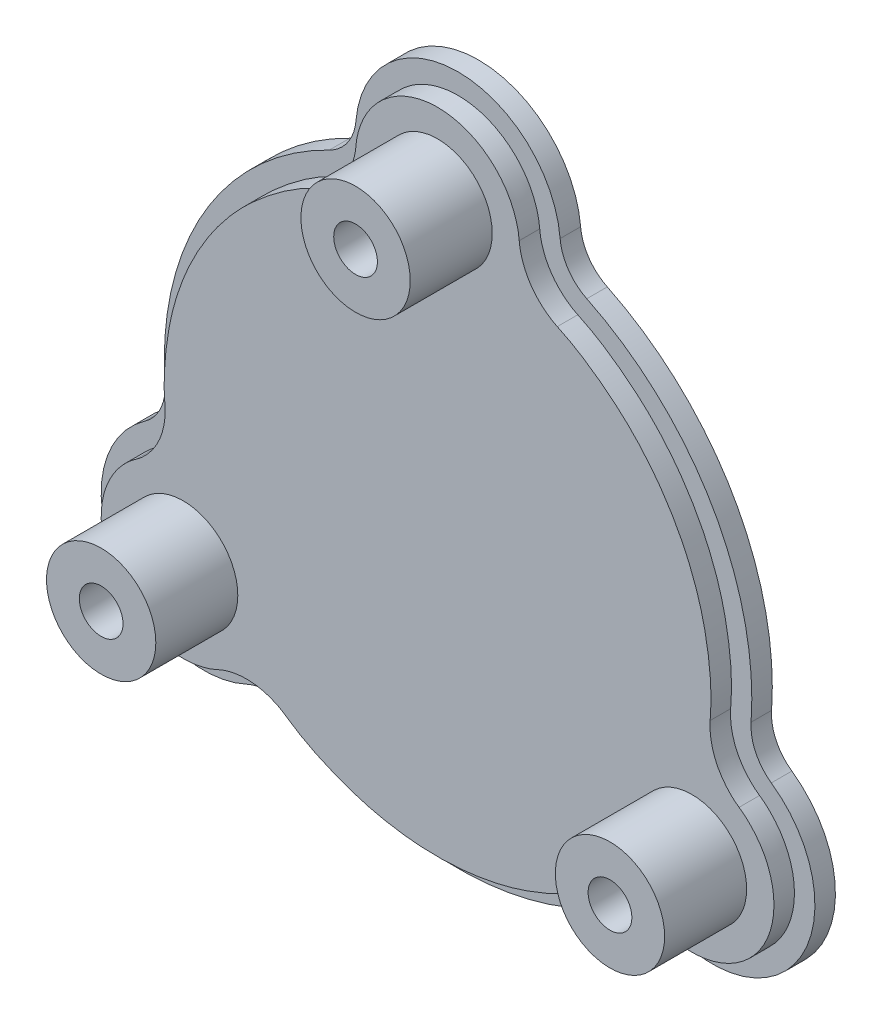
SolidWorks part; units mm, degrees
material "PBT General Purpose"
ref_plane "Front Plane" through (0, 0, 0) normal (0, 0, 1) x (1, 0, 0)
ref_plane "Top Plane" through (0, 0, 0) normal (0, 1, 0) x (1, 0, 0)
ref_plane "Right Plane" through (0, 0, 0) normal (1, 0, 0) x (0, 0, -1)
sketch "Sketch1" plane through (0, 0, 0) normal (0, 0, 1) x (1, 0, 0)
  line L0 (0, 43) -> (0, 82.2622) construction
  line L3 (-37.2391, -21.5) -> (-76.1188, -43.9472) construction
  line L5 (37.2391, -21.5) -> (85.3817, -49.2952) construction
  arc A0 (42.895, -3.0038) -> (18.8462, 38.65) centre (0, 0) ccw
  arc A1 (14.9415, 44.324) -> (-14.9415, 44.324) centre (0, 43) ccw
  arc A2 (-45.8564, -9.2223) -> (-30.915, -35.1017) centre (-37.2391, -21.5) ccw
  arc A3 (30.915, -35.1017) -> (45.8564, -9.2223) centre (37.2391, -21.5) ccw
  arc A4 (-24.0488, -35.6462) -> (24.0488, -35.6462) centre (0, 0) ccw
  arc A5 (-18.8462, 38.65) -> (-42.895, -3.0038) centre (0, 0) ccw
  arc A6 (-14.9415, 44.324) -> (-18.8462, 38.65) centre (-21.9141, 44.9419) cw
  arc A7 (14.9415, 44.324) -> (18.8462, 38.65) centre (21.9141, 44.9419) ccw
  arc A8 (-45.8564, -9.2223) -> (-42.895, -3.0038) centre (-49.8779, -3.4927) ccw
  arc A9 (-30.915, -35.1017) -> (-24.0488, -35.6462) centre (-27.9637, -41.4491) cw
  arc A10 (30.915, -35.1017) -> (24.0488, -35.6462) centre (27.9637, -41.4491) ccw
  arc A11 (45.8564, -9.2223) -> (42.895, -3.0038) centre (49.8779, -3.4927) cw
  dimension "D3" = 86
  dimension "D4" = 15
  dimension "D5" = 7
  dimension "D6" = 7
  dimension "D7" = 7
  dimension "D8" = 7
  dimension "D9" = 7
  dimension "D10" = 7
  dimension "D11" = 43
  dimension "D1" = 120
  dimension "D2" = 120
  dimension "D12" = 43
  dimension "D13" = 43
extrude "Boss-Extrude1" add sketch "Sketch1" along normal blind 3
sketch3d "3DSketch1"
  spline S0 degree 5 poles (-860.3137, -1760.9374, 3) (-312.0144, -671.2908, 3) (-45.6684, -133.8647, 3) (34.2606, 38.4536, 3) (22.9528, 32.5921, 3) (16.6076, 36.45, 3) (16.4124, 36.5792, 3) (15.9342, 36.9172, 3) (15.4777, 37.2817, 3) (15.2128, 37.5106, 3) (14.7035, 37.9899, 3) (14.2399, 38.5149, 3) (14.0199, 38.7878, 3) (13.6041, 39.3524, 3) (13.2379, 39.9504, 3) (13.068, 40.257, 3) (12.7629, 40.8717, 3) (12.515, 41.5106, 3) (12.4065, 41.8284, 3) (12.2465, 42.3606, 3) (12.1161, 42.9018, 3) (12.0708, 43.1168, 3) (12.0158, 43.434, 3) (11.9653, 43.8969, 3) (11.9465, 44.1432, 3) (11.9261, 44.3892, 3) (11.8945, 44.6341, 3) (1998.7254, 253.2621, 2.9942) knots -3.436068 -3.436068 -3.436068 -3.436068 -3.436068 -3.436068 0.056255 0.056255 0.056255 0.1697 0.1697 0.1697 0.339869 0.339869 0.339869 0.510038 0.510038 0.510038 0.680206 0.680206 0.680206 0.843495 0.843495 0.843495 0.95006 0.95006 0.95006 0.999902 1.070242 1.070242 1.070242 1.070242 1.070242 1.070242 only from (17.527, 35.9556, 3) to (11.9531, 44.0602, 3)
  spline S1 degree 5 poles (2004.2193, 217.1358, 3) (789.3192, 95.3125, 3) (192.1624, 39.5792, 3) (3.2218, 27.5195, 3) (13.3064, 37.0339, 3) (11.7927, 45.3074, 3) (11.7316, 45.5816, 3) (11.5576, 46.2624, 3) (11.3448, 46.9302, 3) (11.2018, 47.3252, 3) (10.883, 48.1015, 3) (10.4934, 48.8465, 3) (10.2818, 49.2102, 3) (9.8273, 49.9182, 3) (9.3135, 50.5839, 3) (9.0424, 50.9053, 3) (8.473, 51.5236, 3) (7.8513, 52.0897, 3) (7.5283, 52.359, 3) (6.8595, 52.8686, 3) (6.1487, 53.3178, 3) (5.7837, 53.5267, 3) (5.0365, 53.9122, 3) (4.2584, 54.2308, 3) (3.8626, 54.373, 3) (3.0597, 54.6224, 3) (2.238, 54.8006, 3) (1.8235, 54.8718, 3) (0.9894, 54.9776, 3) (0.1492, 55.0101, 3) (-0.2713, 55.0079, 3) (-1.1111, 54.9669, 3) (-1.9441, 54.8526, 3) (-2.3579, 54.7773, 3) (-3.1777, 54.5907, 3) (-3.9781, 54.3331, 3) (-4.3724, 54.1869, 3) (-5.1472, 53.8604, 3) (-5.8905, 53.4674, 3) (-6.2533, 53.2547, 3) (-6.9595, 52.7984, 3) (-7.623, 52.2819, 3) (-7.9433, 52.0094, 3) (-8.5592, 51.437, 3) (-9.1224, 50.8129, 3) (-9.3902, 50.4888, 3) (-9.8971, 49.8179, 3) (-10.3445, 49.1053, 3) (-10.5523, 48.7395, 3) (-10.9306, 47.9979, 3) (-11.2391, 47.226, 3) (-11.376, 46.8375, 3) (-11.5787, 46.1836, 3) (-11.7442, 45.5178, 3) (-11.802, 45.2514, 3) (-13.2505, 37.1334, 3) (-3.5916, 27.8328, 3) (-192.9693, 39.9975, 3) (-790.1686, 95.5846, 3) (-2004.2932, 216.8589, 3) knots -1.121492 -1.121492 -1.121492 -1.121492 -1.121492 -1.121492 0.019647 0.019647 0.019647 0.058998 0.058998 0.058998 0.118025 0.118025 0.118025 0.177051 0.177051 0.177051 0.236078 0.236078 0.236078 0.295104 0.295104 0.295104 0.354131 0.354131 0.354131 0.413157 0.413157 0.413157 0.472184 0.472184 0.472184 0.53121 0.53121 0.53121 0.590237 0.590237 0.590237 0.649263 0.649263 0.649263 0.70829 0.70829 0.70829 0.767316 0.767316 0.767316 0.826343 0.826343 0.826343 0.885369 0.885369 0.885369 0.943255 0.943255 0.943255 0.981465 0.981465 0.981465 2.100941 2.100941 2.100941 2.100941 2.100941 2.100941 only from (11.9531, 44.0602, 3) to (-11.9532, 44.0592, 3)
  spline S2 degree 5 poles (1979.9765, -133.949, 3) (766.3526, -11.0894, 3) (169.2376, 45.6947, 3) (-20.2646, 58.7915, 3) (-10.7503, 50.3238, 3) (-12.0869, 43.019, 3) (-12.1378, 42.7906, 3) (-12.2828, 42.2232, 3) (-12.4601, 41.6666, 3) (-12.5793, 41.3374, 3) (-12.845, 40.6905, 3) (-13.1697, 40.07, 3) (-13.3461, 39.767, 3) (-13.7248, 39.1769, 3) (-14.1525, 38.6212, 3) (-14.3783, 38.3531, 3) (-14.8433, 37.8484, 3) (-15.3516, 37.3887, 3) (-15.6097, 37.1738, 3) (-16.0496, 36.8343, 3) (-16.5085, 36.5191, 3) (-16.6931, 36.4, 3) (-22.807, 32.7591, 3) (-33.431, 37.9761, 3) (46.96, -135.0822, 3) (312.9624, -672.6898, 3) (859.5004, -1761.281, 3) knots -3.434333 -3.434333 -3.434333 -3.434333 -3.434333 -3.434333 0.056702 0.056702 0.056702 0.170106 0.170106 0.170106 0.340211 0.340211 0.340211 0.510317 0.510317 0.510317 0.680422 0.680422 0.680422 0.84365 0.84365 0.84365 0.950176 0.950176 0.950176 4.299461 4.299461 4.299461 4.299461 4.299461 4.299461 only from (-11.9532, 44.0592, 3) to (-17.5313, 35.9535, 3)
  spline S3 degree 5 poles (-846.1484, 1855.3944, 3) (-303.1451, 751.1079, 3) (-47.1755, 209.3347, 3) (19.9464, 37.6554, 3) (-4.7962, 43.9566, 3) (-21.2263, 33.9675, 3) (-22.0072, 33.4507, 3) (-23.9198, 32.0985, 3) (-25.7454, 30.6405, 3) (-26.8049, 29.7251, 3) (-28.8422, 27.808, 3) (-30.6979, 25.7079, 3) (-31.5785, 24.6163, 3) (-33.2415, 22.3579, 3) (-34.701, 19.9659, 3) (-35.3785, 18.7392, 3) (-36.6258, 16.23, 3) (-37.6521, 13.62, 3) (-38.1073, 12.2934, 3) (-38.8681, 9.7015, 3) (-39.3939, 7.0562, 3) (-39.5966, 5.7731, 3) (-39.8536, 3.6557, 3) (-39.9977, 1.5244, 3) (-40.0312, 0.6913, 3) (-40.144, -17.0171, 3) (-24.9969, -33.9024, 3) (-209.8744, -60.7448, 3) (-807.2354, -109.8368, 3) (-2030.2513, -192.6769, 3) knots -1.874629 -1.874629 -1.874629 -1.874629 -1.874629 -1.874629 0.04914 0.04914 0.04914 0.14742 0.14742 0.14742 0.294839 0.294839 0.294839 0.442259 0.442259 0.442259 0.589678 0.589678 0.589678 0.737098 0.737098 0.737098 0.873872 0.873872 0.873872 0.961506 0.961506 0.961506 2.737832 2.737832 2.737832 2.737832 2.737832 2.737832 only from (-17.5313, 35.9535, 3) to (-39.9023, -2.7942, 3)
  spline S4 degree 5 poles (1955.1838, 135.4163, 3) (737.3662, 65.4332, 3) (138.7654, 27.3824, 3) (-50.4321, 10.4438, 3) (-39.702, 3.5817, 3) (-39.8704, -3.8424, 3) (-39.8847, -4.0761, 3) (-39.9384, -4.6592, 3) (-40.0258, -5.2368, 3) (-40.0915, -5.5806, 3) (-40.2519, -6.2613, 3) (-40.4748, -6.9253, 3) (-40.6012, -7.2523, 3) (-40.8822, -7.8947, 3) (-41.217, -8.5108, 3) (-41.3976, -8.8113, 3) (-41.7773, -9.3829, 3) (-42.2067, -9.917, 3) (-42.4277, -10.1699, 3) (-42.8086, -10.5745, 3) (-43.2121, -10.958, 3) (-43.3756, -11.1048, 3) (-48.8392, -15.6639, 3) (-60.1527, -12.1868, 3) (46.5129, -170.4093, 3) (393.9342, -659.3649, 3) (1105.2373, -1648.1936, 3) knots -3.434333 -3.434333 -3.434333 -3.434333 -3.434333 -3.434333 0.056702 0.056702 0.056702 0.170106 0.170106 0.170106 0.340211 0.340211 0.340211 0.510317 0.510317 0.510317 0.680422 0.680422 0.680422 0.84365 0.84365 0.84365 0.950176 0.950176 0.950176 4.299461 4.299461 4.299461 4.299461 4.299461 4.299461 only from (-39.9023, -2.7942, 3) to (-44.133, -11.6779, 3)
  spline S5 degree 5 poles (-1190.1487, 1627.1296, 3) (-477.2005, 635.9112, 3) (-130.3573, 146.6272, 3) (-25.4435, -10.9696, 3) (-38.7255, -6.9933, 3) (-45.1337, -12.4409, 3) (-45.3406, -12.631, 3) (-45.8432, -13.122, 3) (-46.3152, -13.6403, 3) (-46.5857, -13.9616, 3) (-47.0986, -14.6258, 3) (-47.549, -15.3357, 3) (-47.7582, -15.7008, 3) (-48.1441, -16.4484, 3) (-48.4637, -17.2262, 3) (-48.6065, -17.6217, 3) (-48.8573, -18.424, 3) (-49.0366, -19.2454, 3) (-49.1083, -19.6598, 3) (-49.2153, -20.4939, 3) (-49.2489, -21.334, 3) (-49.2474, -21.7545, 3) (-49.2076, -22.5944, 3) (-49.0944, -23.4275, 3) (-49.0197, -23.8414, 3) (-48.8342, -24.6615, 3) (-48.5777, -25.4622, 3) (-48.4321, -25.8567, 3) (-48.1067, -26.632, 3) (-47.7147, -27.3758, 3) (-47.5026, -27.7389, 3) (-47.0472, -28.4457, 3) (-46.5317, -29.11, 3) (-46.2596, -29.4306, 3) (-45.6881, -30.0473, 3) (-45.0648, -30.6117, 3) (-44.741, -30.88, 3) (-44.0709, -31.3878, 3) (-43.3589, -31.835, 3) (-42.9933, -32.0429, 3) (-42.245, -32.4263, 3) (-41.4659, -32.7427, 3) (-41.0698, -32.8838, 3) (-40.2661, -33.131, 3) (-39.4441, -33.3067, 3) (-39.0295, -33.3765, 3) (-38.195, -33.4801, 3) (-37.3542, -33.5112, 3) (-36.9335, -33.5083, 3) (-36.1021, -33.4651, 3) (-35.2794, -33.3464, 3) (-34.8745, -33.2707, 3) (-34.2069, -33.1193, 3) (-33.5475, -32.9297, 3) (-33.2878, -32.8465, 3) (-25.5333, -30.0419, 3) (-22.3081, -17.0269, 3) (61.8456, -187.1147, 3) (312.3048, -732.0966, 3) (814.3392, -1844.1937, 3) knots -1.12143 -1.12143 -1.12143 -1.12143 -1.12143 -1.12143 0.019675 0.019675 0.019675 0.059025 0.059025 0.059025 0.11805 0.11805 0.11805 0.177075 0.177075 0.177075 0.236099 0.236099 0.236099 0.295124 0.295124 0.295124 0.354149 0.354149 0.354149 0.413174 0.413174 0.413174 0.472199 0.472199 0.472199 0.531224 0.531224 0.531224 0.590248 0.590248 0.590248 0.649273 0.649273 0.649273 0.708298 0.708298 0.708298 0.767323 0.767323 0.767323 0.826348 0.826348 0.826348 0.885373 0.885373 0.885373 0.943257 0.943257 0.943257 0.981466 0.981466 0.981466 2.100909 2.100909 2.100909 2.100909 2.100909 2.100909 only from (-44.133, -11.6779, 3) to (-32.1798, -32.3813, 3)
  spline S6 degree 5 poles (-873.9817, 1781.6769, 3) (-373.5713, 669.2226, 3) (-124.1912, 123.716, 3) (-40.7826, -46.9454, 3) (-38.2065, -34.472, 3) (-31.2121, -31.9771, 3) (-30.9888, -31.907, 3) (-30.425, -31.7488, 3) (-29.8543, -31.6241, 3) (-29.5097, -31.5627, 3) (-28.8165, -31.4693, 3) (-28.1168, -31.4403, 3) (-27.7662, -31.4415, 3) (-27.0658, -31.4745, 3) (-26.3707, -31.5671, 3) (-26.0256, -31.6285, 3) (-25.356, -31.7789, 3) (-24.7038, -31.9892, 3) (-24.3886, -32.1053, 3) (-23.8746, -32.3165, 3) (-23.3723, -32.5563, 3) (-23.1768, -32.6567, 3) (-22.8959, -32.8138, 3) (-22.626, -32.9881, 3) (-22.348, -33.173, 3) (-22.0739, -33.364, 3) (-21.7909, -33.5411, 3) (-24.1044, -37.5263, 3) (1068.169, 1643.053, 2.9998) knots -3.433006 -3.433006 -3.433006 -3.433006 -3.433006 -3.433006 0.05668 0.05668 0.05668 0.17004 0.17004 0.17004 0.34008 0.34008 0.34008 0.51012 0.51012 0.51012 0.68016 0.68016 0.68016 0.843325 0.843325 0.843325 0.94981 0.94981 0.94981 0.999615 0.999615 1.112235 1.112235 1.112235 1.112235 1.112235 1.112235 only from (-32.1798, -32.3813, 3) to (-22.3677, -33.1615, 3)
  spline S7 degree 5 poles (-1183.7516, -1660.4941, 3) (-498.9088, -638.0895, 3) (-157.7022, -145.5234, 3) (-42.5837, -1.5535, 3) (-35.6695, -26.1319, 3) (-18.8036, -35.3663, 3) (-17.9656, -35.7841, 3) (-15.8382, -36.7644, 3) (-13.6627, -37.6165, 3) (-12.3403, -38.0763, 3) (-9.6613, -38.8821, 3) (-6.9148, -39.4391, 3) (-5.5291, -39.6559, 3) (-2.7418, -39.9669, 3) (0.0596, -40.0349, 3) (1.4606, -40.0083, 3) (4.2574, -39.8339, 3) (7.0308, -39.4177, 3) (8.4072, -39.1486, 3) (11.0323, -38.5115, 3) (13.5861, -37.6442, 3) (14.7986, -37.1783, 3) (16.7609, -36.3421, 3) (18.6787, -35.4012, 3) (19.4169, -35.0137, 3) (34.8093, -26.2572, 3) (41.8588, -4.6967, 3) (157.5442, -151.3847, 3) (498.7411, -644.1707, 3) (1181.9934, -1661.9178, 3) knots -1.874873 -1.874873 -1.874873 -1.874873 -1.874873 -1.874873 0.04906 0.04906 0.04906 0.147348 0.147348 0.147348 0.29478 0.29478 0.29478 0.442212 0.442212 0.442212 0.589644 0.589644 0.589644 0.737076 0.737076 0.737076 0.873861 0.873861 0.873861 0.961502 0.961502 0.961502 2.73798 2.73798 2.73798 2.73798 2.73798 2.73798 only from (-22.3677, -33.1615, 3) to (22.371, -33.1593, 3)
  spline S8 degree 5 poles (-1094.8644, 1625.5285, 3) (-425.3493, 605.8603, 3) (-93.0964, 106.4829, 3) (16.1715, -48.8973, 3) (16.7492, -36.1738, 3) (23.2628, -32.6076, 3) (23.4723, -32.5031, 3) (24.0042, -32.258, 3) (24.5481, -32.045, 3) (24.8787, -31.93, 3) (25.5484, -31.7285, 3) (26.2349, -31.5896, 3) (26.5813, -31.5355, 3) (27.2781, -31.4577, 3) (27.9791, -31.4395, 3) (28.3296, -31.4458, 3) (29.0145, -31.4888, 3) (29.6917, -31.5936, 3) (30.0213, -31.6585, 3) (30.5621, -31.7861, 3) (31.096, -31.9437, 3) (31.3048, -32.012, 3) (31.607, -32.1229, 3) (32.0421, -32.3146, 3) (32.2733, -32.426, 3) (32.5055, -32.5353, 3) (32.7428, -32.6329, 3) (-779.0835, -1858.7335, 2.9474) knots -3.433937 -3.433937 -3.433937 -3.433937 -3.433937 -3.433937 0.056695 0.056695 0.056695 0.170086 0.170086 0.170086 0.340172 0.340172 0.340172 0.510258 0.510258 0.510258 0.680344 0.680344 0.680344 0.843553 0.843553 0.843553 0.950067 0.950067 0.950067 0.999885 1.074913 1.074913 1.074913 1.074913 1.074913 1.074913 only from (22.371, -33.1593, 3) to (32.1809, -32.3818, 3)
  spline S9 degree 5 poles (-814.0955, -1844.3412, 3) (-312.1289, -731.2536, 3) (-61.8077, -186.2134, 3) (22.2216, -16.5495, 3) (25.419, -30.0406, 3) (33.341, -32.8665, 3) (33.609, -32.9506, 3) (34.2856, -33.1404, 3) (34.9704, -33.29, 3) (35.3839, -33.3637, 3) (36.2157, -33.4757, 3) (37.0556, -33.5108, 3) (37.4763, -33.5094, 3) (38.3168, -33.4698, 3) (39.1502, -33.3577, 3) (39.5641, -33.2836, 3) (40.3843, -33.0996, 3) (41.1853, -32.8443, 3) (41.5801, -32.6991, 3) (42.3559, -32.3748, 3) (43.1002, -31.9838, 3) (43.4637, -31.7722, 3) (44.1711, -31.3178, 3) (44.836, -30.8032, 3) (45.1571, -30.5316, 3) (45.7746, -29.961, 3) (46.3398, -29.3385, 3) (46.6086, -29.0151, 3) (47.1173, -28.3456, 3) (47.5655, -27.6342, 3) (47.7739, -27.269, 3) (48.1583, -26.5212, 3) (48.4758, -25.7426, 3) (48.6174, -25.3467, 3) (48.8658, -24.5434, 3) (49.0429, -23.7214, 3) (49.1134, -23.3068, 3) (49.2181, -22.4726, 3) (49.2493, -21.6324, 3) (49.2466, -21.2119, 3) (49.2045, -20.3721, 3) (49.089, -19.5392, 3) (49.0131, -19.1256, 3) (48.8254, -18.306, 3) (48.5665, -17.5063, 3) (48.4196, -17.1123, 3) (48.0921, -16.3378, 3) (47.6987, -15.5941, 3) (47.4858, -15.2312, 3) (47.0327, -14.5327, 3) (46.5185, -13.8796, 3) (46.2505, -13.5669, 3) (45.7856, -13.0644, 3) (45.2917, -12.5881, 3) (45.0898, -12.4048, 3) (38.7837, -7.0915, 3) (25.8998, -10.806, 3) (131.1235, 147.1175, 3) (477.8628, 636.5135, 3) (1189.9515, 1627.3385, 3) knots -1.121517 -1.121517 -1.121517 -1.121517 -1.121517 -1.121517 0.019642 0.019642 0.019642 0.058994 0.058994 0.058994 0.11802 0.11802 0.11802 0.177047 0.177047 0.177047 0.236074 0.236074 0.236074 0.295101 0.295101 0.295101 0.354128 0.354128 0.354128 0.413154 0.413154 0.413154 0.472181 0.472181 0.472181 0.531208 0.531208 0.531208 0.590235 0.590235 0.590235 0.649262 0.649262 0.649262 0.708288 0.708288 0.708288 0.767315 0.767315 0.767315 0.826342 0.826342 0.826342 0.885369 0.885369 0.885369 0.943255 0.943255 0.943255 0.981465 0.981465 0.981465 2.100947 2.100947 2.100947 2.100947 2.100947 2.100947 only from (32.1809, -32.3818, 3) to (44.133, -11.6779, 3)
  spline S10 degree 5 poles (-1105.9949, -1647.7403, 3) (-392.7814, -658.1381, 3) (-45.0464, -169.4119, 3) (61.0472, -11.8461, 3) (48.9569, -15.8518, 3) (43.299, -11.042, 3) (43.1266, -10.8836, 3) (42.7077, -10.4744, 3) (42.3144, -10.0425, 3) (42.0889, -9.7748, 3) (41.6615, -9.2212, 3) (41.2865, -8.6297, 3) (41.1123, -8.3255, 3) (40.7906, -7.7024, 3) (40.5232, -7.0542, 3) (40.4039, -6.7246, 3) (40.1994, -6.0695, 3) (40.0554, -5.3995, 3) (39.9983, -5.0685, 3) (39.9242, -4.5178, 3) (39.8807, -3.9628, 3) (39.8699, -3.7434, 3) (39.8656, -3.4215, 3) (39.8815, -3.1006, 3) (39.9028, -2.7638, 3) (39.9316, -2.4274, 3) (39.9432, -2.09, 3) (44.6594, -2.1031, 3) (-1956.8344, 103.5873, 2.9998) knots -3.432962 -3.432962 -3.432962 -3.432962 -3.432962 -3.432962 0.056679 0.056679 0.056679 0.170038 0.170038 0.170038 0.340075 0.340075 0.340075 0.510113 0.510113 0.510113 0.68015 0.68015 0.68015 0.843313 0.843313 0.843313 0.949796 0.949796 0.949796 0.9996 0.9996 1.113983 1.113983 1.113983 1.113983 1.113983 1.113983 only from (44.133, -11.6779, 3) to (39.9026, -2.7901, 3)
  spline S11 degree 5 poles (2029.9204, -194.9129, 3) (802.0618, -113.0234, 3) (204.8794, -63.8126, 3) (22.6372, -36.1019, 3) (40.4656, -17.8248, 3) (40.0299, 1.3988, 3) (39.9728, 2.3334, 3) (39.758, 4.6659, 3) (39.4082, 6.9759, 3) (39.1451, 8.3511, 3) (38.5036, 11.0741, 3) (37.6127, 13.7312, 3) (37.1076, 15.0396, 3) (35.9833, 17.609, 3) (34.6415, 20.069, 3) (33.9179, 21.2691, 3) (32.3685, 23.6039, 3) (30.6213, 25.7977, 3) (29.7001, 26.8552, 3) (27.8358, 28.81, 3) (25.8078, 30.588, 3) (24.798, 31.4051, 3) (23.0927, 32.6864, 3) (21.319, 33.8768, 3) (20.6143, 34.3224, 3) (19.5804, 34.9281, 3) (18.5148, 35.4715, 3) (17.8064, 35.8222, 3) (17.0933, 36.1638, 3) (16.3856, 36.516, 3) (14.6341, 34.006, 3) (919.7812, 1817.2964, 2.9992) knots -1.874697 -1.874697 -1.874697 -1.874697 -1.874697 -1.874697 0.049052 0.049052 0.049052 0.147331 0.147331 0.147331 0.294748 0.294748 0.294748 0.442165 0.442165 0.442165 0.589583 0.589583 0.589583 0.737 0.737 0.737 0.873772 0.873772 0.873772 0.961405 0.961405 0.961405 0.999899 0.999899 1.044758 1.044758 1.044758 1.044758 1.044758 1.044758 only from (39.9026, -2.7901, 3) to (17.527, 35.9556, 3)
  spline S12 degree 5 poles (17.527, 35.9556, 3) (17.4231, 36.0062, 3) (17.3193, 36.0569, 3) (17.2158, 36.1084, 3) (16.9062, 36.2684, 3) (16.6076, 36.45, 3) (16.4124, 36.5792, 3) (15.9342, 36.9172, 3) (15.4777, 37.2817, 3) (15.2128, 37.5106, 3) (14.7035, 37.9899, 3) (14.2399, 38.5149, 3) (14.0199, 38.7878, 3) (13.6041, 39.3524, 3) (13.2379, 39.9504, 3) (13.068, 40.257, 3) (12.7629, 40.8717, 3) (12.515, 41.5106, 3) (12.4065, 41.8284, 3) (12.2465, 42.3606, 3) (12.1161, 42.9018, 3) (12.0708, 43.1168, 3) (12.0158, 43.434, 3) (11.9809, 43.7535, 3) (11.9712, 43.8556, 3) (11.9621, 43.9578, 3) (11.9531, 44.06, 3) (11.9531, 44.0602, 3) knots 0 0 0 0 0 0 0.056255 0.056255 0.056255 0.1697 0.1697 0.1697 0.339869 0.339869 0.339869 0.510038 0.510038 0.510038 0.680206 0.680206 0.680206 0.843495 0.843495 0.843495 0.95006 0.95006 0.95006 0.999902 1 1 1 1 1 1
  spline S13 degree 5 poles (11.9531, 44.0602, 3) (11.9408, 44.1993, 3) (11.9284, 44.3383, 3) (11.915, 44.4773, 3) (11.8683, 44.8939, 3) (11.7927, 45.3074, 3) (11.7316, 45.5816, 3) (11.5576, 46.2624, 3) (11.3448, 46.9302, 3) (11.2018, 47.3252, 3) (10.883, 48.1015, 3) (10.4934, 48.8465, 3) (10.2818, 49.2102, 3) (9.8273, 49.9182, 3) (9.3135, 50.5839, 3) (9.0424, 50.9053, 3) (8.473, 51.5236, 3) (7.8513, 52.0897, 3) (7.5283, 52.359, 3) (6.8595, 52.8686, 3) (6.1487, 53.3178, 3) (5.7837, 53.5267, 3) (5.0365, 53.9122, 3) (4.2584, 54.2308, 3) (3.8626, 54.373, 3) (3.0597, 54.6224, 3) (2.238, 54.8006, 3) (1.8235, 54.8718, 3) (0.9894, 54.9776, 3) (0.1492, 55.0101, 3) (-0.2713, 55.0079, 3) (-1.1111, 54.9669, 3) (-1.9441, 54.8526, 3) (-2.3579, 54.7773, 3) (-3.1777, 54.5907, 3) (-3.9781, 54.3331, 3) (-4.3724, 54.1869, 3) (-5.1472, 53.8604, 3) (-5.8905, 53.4674, 3) (-6.2533, 53.2547, 3) (-6.9595, 52.7984, 3) (-7.623, 52.2819, 3) (-7.9433, 52.0094, 3) (-8.5592, 51.437, 3) (-9.1224, 50.8129, 3) (-9.3902, 50.4888, 3) (-9.8971, 49.8179, 3) (-10.3445, 49.1053, 3) (-10.5523, 48.7395, 3) (-10.9306, 47.9979, 3) (-11.2391, 47.226, 3) (-11.376, 46.8375, 3) (-11.5787, 46.1836, 3) (-11.7442, 45.5178, 3) (-11.802, 45.2514, 3) (-11.873, 44.8534, 3) (-11.9173, 44.4527, 3) (-11.9299, 44.3216, 3) (-11.9415, 44.1904, 3) (-11.9532, 44.0592, 3) knots 0 0 0 0 0 0 0.019647 0.019647 0.019647 0.058998 0.058998 0.058998 0.118025 0.118025 0.118025 0.177051 0.177051 0.177051 0.236078 0.236078 0.236078 0.295104 0.295104 0.295104 0.354131 0.354131 0.354131 0.413157 0.413157 0.413157 0.472184 0.472184 0.472184 0.53121 0.53121 0.53121 0.590237 0.590237 0.590237 0.649263 0.649263 0.649263 0.70829 0.70829 0.70829 0.767316 0.767316 0.767316 0.826343 0.826343 0.826343 0.885369 0.885369 0.885369 0.943255 0.943255 0.943255 0.981465 0.981465 0.981465 1 1 1 1 1 1
  spline S14 degree 5 poles (-11.9532, 44.0592, 3) (-11.9634, 43.9431, 3) (-11.9737, 43.8271, 3) (-11.9849, 43.7111, 3) (-12.0238, 43.3638, 3) (-12.0869, 43.019, 3) (-12.1378, 42.7906, 3) (-12.2828, 42.2232, 3) (-12.4601, 41.6666, 3) (-12.5793, 41.3374, 3) (-12.845, 40.6905, 3) (-13.1697, 40.07, 3) (-13.3461, 39.767, 3) (-13.7248, 39.1769, 3) (-14.1525, 38.6212, 3) (-14.3783, 38.3531, 3) (-14.8433, 37.8484, 3) (-15.3516, 37.3887, 3) (-15.6097, 37.1738, 3) (-16.0496, 36.8343, 3) (-16.5085, 36.5191, 3) (-16.6931, 36.4, 3) (-16.9697, 36.2353, 3) (-17.2555, 36.0887, 3) (-17.3473, 36.0432, 3) (-17.4393, 35.9984, 3) (-17.5313, 35.9535, 3) knots 0 0 0 0 0 0 0.056702 0.056702 0.056702 0.170106 0.170106 0.170106 0.340211 0.340211 0.340211 0.510317 0.510317 0.510317 0.680422 0.680422 0.680422 0.84365 0.84365 0.84365 0.950176 0.950176 0.950176 1 1 1 1 1 1
  spline S15 degree 5 poles (-17.5313, 35.9535, 3) (-17.9502, 35.7492, 3) (-18.3692, 35.5449, 3) (-18.7864, 35.3375, 3) (-20.0285, 34.6958, 3) (-21.2263, 33.9675, 3) (-22.0072, 33.4507, 3) (-23.9198, 32.0985, 3) (-25.7454, 30.6405, 3) (-26.8049, 29.7251, 3) (-28.8422, 27.808, 3) (-30.6979, 25.7079, 3) (-31.5785, 24.6163, 3) (-33.2415, 22.3579, 3) (-34.701, 19.9659, 3) (-35.3785, 18.7392, 3) (-36.6258, 16.23, 3) (-37.6521, 13.62, 3) (-38.1073, 12.2934, 3) (-38.8681, 9.7015, 3) (-39.3939, 7.0562, 3) (-39.5966, 5.7731, 3) (-39.8536, 3.6557, 3) (-39.9977, 1.5244, 3) (-40.0312, 0.6913, 3) (-40.0389, -0.5069, 3) (-39.9766, -1.7014, 3) (-39.9533, -2.0658, 3) (-39.9278, -2.43, 3) (-39.9023, -2.7942, 3) knots 0 0 0 0 0 0 0.04914 0.04914 0.04914 0.14742 0.14742 0.14742 0.294839 0.294839 0.294839 0.442259 0.442259 0.442259 0.589678 0.589678 0.589678 0.737098 0.737098 0.737098 0.873872 0.873872 0.873872 0.961506 0.961506 0.961506 1 1 1 1 1 1
  spline S16 degree 5 poles (-39.9023, -2.7942, 3) (-39.8941, -2.9104, 3) (-39.886, -3.0267, 3) (-39.8788, -3.1429, 3) (-39.8624, -3.4921, 3) (-39.8704, -3.8424, 3) (-39.8847, -4.0761, 3) (-39.9384, -4.6592, 3) (-40.0258, -5.2368, 3) (-40.0915, -5.5806, 3) (-40.2519, -6.2613, 3) (-40.4748, -6.9253, 3) (-40.6012, -7.2523, 3) (-40.8822, -7.8947, 3) (-41.217, -8.5108, 3) (-41.3976, -8.8113, 3) (-41.7773, -9.3829, 3) (-42.2067, -9.917, 3) (-42.4277, -10.1699, 3) (-42.8086, -10.5745, 3) (-43.2121, -10.958, 3) (-43.3756, -11.1048, 3) (-43.6228, -11.311, 3) (-43.882, -11.5008, 3) (-43.9654, -11.5602, 3) (-44.0492, -11.619, 3) (-44.133, -11.6779, 3) knots 0 0 0 0 0 0 0.056702 0.056702 0.056702 0.170106 0.170106 0.170106 0.340211 0.340211 0.340211 0.510317 0.510317 0.510317 0.680422 0.680422 0.680422 0.84365 0.84365 0.84365 0.950176 0.950176 0.950176 1 1 1 1 1 1
  spline S17 degree 5 poles (-44.133, -11.6779, 3) (-44.2474, -11.7582, 3) (-44.3619, -11.8385, 3) (-44.4757, -11.9197, 3) (-44.8133, -12.1685, 3) (-45.1337, -12.4409, 3) (-45.3406, -12.631, 3) (-45.8432, -13.122, 3) (-46.3152, -13.6403, 3) (-46.5857, -13.9616, 3) (-47.0986, -14.6258, 3) (-47.549, -15.3357, 3) (-47.7582, -15.7008, 3) (-48.1441, -16.4484, 3) (-48.4637, -17.2262, 3) (-48.6065, -17.6217, 3) (-48.8573, -18.424, 3) (-49.0366, -19.2454, 3) (-49.1083, -19.6598, 3) (-49.2153, -20.4939, 3) (-49.2489, -21.334, 3) (-49.2474, -21.7545, 3) (-49.2076, -22.5944, 3) (-49.0944, -23.4275, 3) (-49.0197, -23.8414, 3) (-48.8342, -24.6615, 3) (-48.5777, -25.4622, 3) (-48.4321, -25.8567, 3) (-48.1067, -26.632, 3) (-47.7147, -27.3758, 3) (-47.5026, -27.7389, 3) (-47.0472, -28.4457, 3) (-46.5317, -29.11, 3) (-46.2596, -29.4306, 3) (-45.6881, -30.0473, 3) (-45.0648, -30.6117, 3) (-44.741, -30.88, 3) (-44.0709, -31.3878, 3) (-43.3589, -31.835, 3) (-42.9933, -32.0429, 3) (-42.245, -32.4263, 3) (-41.4659, -32.7427, 3) (-41.0698, -32.8838, 3) (-40.2661, -33.131, 3) (-39.4441, -33.3067, 3) (-39.0295, -33.3765, 3) (-38.195, -33.4801, 3) (-37.3542, -33.5112, 3) (-36.9335, -33.5083, 3) (-36.1021, -33.4651, 3) (-35.2794, -33.3464, 3) (-34.8745, -33.2707, 3) (-34.2069, -33.1193, 3) (-33.5475, -32.9297, 3) (-33.2878, -32.8465, 3) (-32.9077, -32.7091, 3) (-32.5385, -32.5471, 3) (-32.4187, -32.4924, 3) (-32.2992, -32.4369, 3) (-32.1798, -32.3813, 3) knots 0 0 0 0 0 0 0.019675 0.019675 0.019675 0.059025 0.059025 0.059025 0.11805 0.11805 0.11805 0.177075 0.177075 0.177075 0.236099 0.236099 0.236099 0.295124 0.295124 0.295124 0.354149 0.354149 0.354149 0.413174 0.413174 0.413174 0.472199 0.472199 0.472199 0.531224 0.531224 0.531224 0.590248 0.590248 0.590248 0.649273 0.649273 0.649273 0.708298 0.708298 0.708298 0.767323 0.767323 0.767323 0.826348 0.826348 0.826348 0.885373 0.885373 0.885373 0.943257 0.943257 0.943257 0.981466 0.981466 0.981466 1 1 1 1 1 1
  spline S18 degree 5 poles (-32.1798, -32.3813, 3) (-32.0741, -32.3322, 3) (-31.9685, -32.2831, 3) (-31.8625, -32.2348, 3) (-31.5422, -32.0948, 3) (-31.2121, -31.9771, 3) (-30.9888, -31.907, 3) (-30.425, -31.7488, 3) (-29.8543, -31.6241, 3) (-29.5097, -31.5627, 3) (-28.8165, -31.4693, 3) (-28.1168, -31.4403, 3) (-27.7662, -31.4415, 3) (-27.0658, -31.4745, 3) (-26.3707, -31.5671, 3) (-26.0256, -31.6285, 3) (-25.356, -31.7789, 3) (-24.7038, -31.9892, 3) (-24.3886, -32.1053, 3) (-23.8746, -32.3165, 3) (-23.3723, -32.5563, 3) (-23.1768, -32.6567, 3) (-22.8959, -32.8138, 3) (-22.626, -32.9881, 3) (-22.5401, -33.0452, 3) (-22.4545, -33.1029, 3) (-22.369, -33.1606, 3) (-22.3684, -33.1611, 3) (-22.3677, -33.1615, 3) knots 0 0 0 0 0 0 0.05668 0.05668 0.05668 0.17004 0.17004 0.17004 0.34008 0.34008 0.34008 0.51012 0.51012 0.51012 0.68016 0.68016 0.68016 0.843325 0.843325 0.843325 0.94981 0.94981 0.94981 0.999615 0.999615 1 1 1 1 1 1
  spline S19 degree 5 poles (-22.3677, -33.1615, 3) (-21.982, -33.4217, 3) (-21.5963, -33.6819, 3) (-21.2086, -33.9391, 3) (-20.0325, -34.6934, 3) (-18.8036, -35.3663, 3) (-17.9656, -35.7841, 3) (-15.8382, -36.7644, 3) (-13.6627, -37.6165, 3) (-12.3403, -38.0763, 3) (-9.6613, -38.8821, 3) (-6.9148, -39.4391, 3) (-5.5291, -39.6559, 3) (-2.7418, -39.9669, 3) (0.0596, -40.0349, 3) (1.4606, -40.0083, 3) (4.2574, -39.8339, 3) (7.0308, -39.4177, 3) (8.4072, -39.1486, 3) (11.0323, -38.5115, 3) (13.5861, -37.6442, 3) (14.7986, -37.1783, 3) (16.7609, -36.3421, 3) (18.6787, -35.4012, 3) (19.4169, -35.0137, 3) (20.4585, -34.4212, 3) (21.4618, -33.7701, 3) (21.7657, -33.5677, 3) (22.0683, -33.3635, 3) (22.371, -33.1593, 3) knots 0 0 0 0 0 0 0.04906 0.04906 0.04906 0.147348 0.147348 0.147348 0.29478 0.29478 0.29478 0.442212 0.442212 0.442212 0.589644 0.589644 0.589644 0.737076 0.737076 0.737076 0.873861 0.873861 0.873861 0.961502 0.961502 0.961502 1 1 1 1 1 1
  spline S20 degree 5 poles (22.371, -33.1593, 3) (22.4676, -33.0941, 3) (22.5642, -33.029, 3) (22.6612, -32.9646, 3) (22.9554, -32.7759, 3) (23.2628, -32.6076, 3) (23.4723, -32.5031, 3) (24.0042, -32.258, 3) (24.5481, -32.045, 3) (24.8787, -31.93, 3) (25.5484, -31.7285, 3) (26.2349, -31.5896, 3) (26.5813, -31.5355, 3) (27.2781, -31.4577, 3) (27.9791, -31.4395, 3) (28.3296, -31.4458, 3) (29.0145, -31.4888, 3) (29.6917, -31.5936, 3) (30.0213, -31.6585, 3) (30.5621, -31.7861, 3) (31.096, -31.9437, 3) (31.3048, -32.012, 3) (31.607, -32.1229, 3) (31.9012, -32.2526, 3) (31.9946, -32.2952, 3) (32.0876, -32.3385, 3) (32.1807, -32.3817, 3) (32.1809, -32.3818, 3) knots 0 0 0 0 0 0 0.056695 0.056695 0.056695 0.170086 0.170086 0.170086 0.340172 0.340172 0.340172 0.510258 0.510258 0.510258 0.680344 0.680344 0.680344 0.843553 0.843553 0.843553 0.950067 0.950067 0.950067 0.999885 1 1 1 1 1 1
  spline S21 degree 5 poles (32.1809, -32.3818, 3) (32.3074, -32.4407, 3) (32.434, -32.4995, 3) (32.561, -32.5574, 3) (32.9451, -32.7252, 3) (33.341, -32.8665, 3) (33.609, -32.9506, 3) (34.2856, -33.1404, 3) (34.9704, -33.29, 3) (35.3839, -33.3637, 3) (36.2157, -33.4757, 3) (37.0556, -33.5108, 3) (37.4763, -33.5094, 3) (38.3168, -33.4698, 3) (39.1502, -33.3577, 3) (39.5641, -33.2836, 3) (40.3843, -33.0996, 3) (41.1853, -32.8443, 3) (41.5801, -32.6991, 3) (42.3559, -32.3748, 3) (43.1002, -31.9838, 3) (43.4637, -31.7722, 3) (44.1711, -31.3178, 3) (44.836, -30.8032, 3) (45.1571, -30.5316, 3) (45.7746, -29.961, 3) (46.3398, -29.3385, 3) (46.6086, -29.0151, 3) (47.1173, -28.3456, 3) (47.5655, -27.6342, 3) (47.7739, -27.269, 3) (48.1583, -26.5212, 3) (48.4758, -25.7426, 3) (48.6174, -25.3467, 3) (48.8658, -24.5434, 3) (49.0429, -23.7214, 3) (49.1134, -23.3068, 3) (49.2181, -22.4726, 3) (49.2493, -21.6324, 3) (49.2466, -21.2119, 3) (49.2045, -20.3721, 3) (49.089, -19.5392, 3) (49.0131, -19.1256, 3) (48.8254, -18.306, 3) (48.5665, -17.5063, 3) (48.4196, -17.1123, 3) (48.0921, -16.3378, 3) (47.6987, -15.5941, 3) (47.4858, -15.2312, 3) (47.0327, -14.5327, 3) (46.5185, -13.8796, 3) (46.2505, -13.5669, 3) (45.7856, -13.0644, 3) (45.2917, -12.5881, 3) (45.0898, -12.4048, 3) (44.7807, -12.1444, 3) (44.4558, -11.9056, 3) (44.3486, -11.8292, 3) (44.2408, -11.7535, 3) (44.133, -11.6779, 3) knots 0 0 0 0 0 0 0.019642 0.019642 0.019642 0.058994 0.058994 0.058994 0.11802 0.11802 0.11802 0.177047 0.177047 0.177047 0.236074 0.236074 0.236074 0.295101 0.295101 0.295101 0.354128 0.354128 0.354128 0.413154 0.413154 0.413154 0.472181 0.472181 0.472181 0.531208 0.531208 0.531208 0.590235 0.590235 0.590235 0.649262 0.649262 0.649262 0.708288 0.708288 0.708288 0.767315 0.767315 0.767315 0.826342 0.826342 0.826342 0.885369 0.885369 0.885369 0.943255 0.943255 0.943255 0.981465 0.981465 0.981465 1 1 1 1 1 1
  spline S22 degree 5 poles (44.133, -11.6779, 3) (44.0376, -11.6109, 3) (43.9422, -11.544, 3) (43.8474, -11.4763, 3) (43.566, -11.269, 3) (43.299, -11.042, 3) (43.1266, -10.8836, 3) (42.7077, -10.4744, 3) (42.3144, -10.0425, 3) (42.0889, -9.7748, 3) (41.6615, -9.2212, 3) (41.2865, -8.6297, 3) (41.1123, -8.3255, 3) (40.7906, -7.7024, 3) (40.5232, -7.0542, 3) (40.4039, -6.7246, 3) (40.1994, -6.0695, 3) (40.0554, -5.3995, 3) (39.9983, -5.0685, 3) (39.9242, -4.5178, 3) (39.8807, -3.9628, 3) (39.8699, -3.7434, 3) (39.8656, -3.4215, 3) (39.8815, -3.1006, 3) (39.888, -2.9976, 3) (39.8952, -2.8947, 3) (39.9025, -2.7917, 3) (39.9025, -2.7909, 3) (39.9026, -2.7901, 3) knots 0 0 0 0 0 0 0.056679 0.056679 0.056679 0.170038 0.170038 0.170038 0.340075 0.340075 0.340075 0.510113 0.510113 0.510113 0.68015 0.68015 0.68015 0.843313 0.843313 0.843313 0.949796 0.949796 0.949796 0.9996 0.9996 1 1 1 1 1 1
  spline S23 degree 5 poles (39.9026, -2.7901, 3) (39.9351, -2.326, 3) (39.9676, -1.8619, 3) (39.9964, -1.3976, 3) (40.0617, -0.0019, 3) (40.0299, 1.3988, 3) (39.9728, 2.3334, 3) (39.758, 4.6659, 3) (39.4082, 6.9759, 3) (39.1451, 8.3511, 3) (38.5036, 11.0741, 3) (37.6127, 13.7312, 3) (37.1076, 15.0396, 3) (35.9833, 17.609, 3) (34.6415, 20.069, 3) (33.9179, 21.2691, 3) (32.3685, 23.6039, 3) (30.6213, 25.7977, 3) (29.7001, 26.8552, 3) (27.8358, 28.81, 3) (25.8078, 30.588, 3) (24.798, 31.4051, 3) (23.0927, 32.6864, 3) (21.319, 33.8768, 3) (20.6143, 34.3224, 3) (19.5804, 34.9281, 3) (18.5148, 35.4715, 3) (18.1868, 35.6339, 3) (17.8577, 35.7943, 3) (17.5287, 35.9548, 3) (17.5278, 35.9552, 3) (17.527, 35.9556, 3) knots 0 0 0 0 0 0 0.049052 0.049052 0.049052 0.147331 0.147331 0.147331 0.294748 0.294748 0.294748 0.442165 0.442165 0.442165 0.589583 0.589583 0.589583 0.737 0.737 0.737 0.873772 0.873772 0.873772 0.961405 0.961405 0.961405 0.999899 0.999899 1 1 1 1 1 1
  dimension "D1" = 3
extrude "Boss-Extrude2" add sketch "3DSketch1" along direction (0, 0, -1) on the side of the normal blind 3
sketch "Sketch4" plane through (0, 0, 6) normal (0, 0, 1) x (1, 0, 0)
  circle A0 centre (0, 43) radius 8
  circle A1 centre (37.2391, -21.5) radius 8
  circle A2 centre (-37.2391, -21.5) radius 8
  arc A12 (-18.8462, 38.65) -> (-14.9415, 44.324) centre (-21.9141, 44.9419) ccw
  arc A13 (-18.8462, 38.65) -> (-42.895, -3.0038) centre (0, 0) ccw
  arc A14 (-45.8564, -9.2223) -> (-42.895, -3.0038) centre (-49.8779, -3.4927) ccw
  arc A15 (-45.8564, -9.2223) -> (-30.915, -35.1017) centre (-37.2391, -21.5) ccw
  arc A16 (-24.0488, -35.6462) -> (-30.915, -35.1017) centre (-27.9637, -41.4491) ccw
  arc A17 (-24.0488, -35.6462) -> (24.0488, -35.6462) centre (0, 0) ccw
  arc A18 (30.915, -35.1017) -> (24.0488, -35.6462) centre (27.9637, -41.4491) ccw
  arc A19 (30.915, -35.1017) -> (45.8564, -9.2223) centre (37.2391, -21.5) ccw
  arc A20 (42.895, -3.0038) -> (45.8564, -9.2223) centre (49.8779, -3.4927) ccw
  arc A21 (42.895, -3.0038) -> (18.8462, 38.65) centre (0, 0) ccw
  arc A22 (14.9415, 44.324) -> (18.8462, 38.65) centre (21.9141, 44.9419) ccw
  arc A23 (14.9415, 44.324) -> (-14.9415, 44.324) centre (0, 43) ccw
  arc A24 (-18.8462, 38.65) -> (-14.9415, 44.324) centre (-21.9141, 44.9419) ccw construction
  arc A25 (-18.8462, 38.65) -> (-42.895, -3.0038) centre (0, 0) ccw construction
  arc A26 (-45.8564, -9.2223) -> (-42.895, -3.0038) centre (-49.8779, -3.4927) ccw construction
  arc A27 (-45.8564, -9.2223) -> (-30.915, -35.1017) centre (-37.2391, -21.5) ccw construction
  arc A28 (-24.0488, -35.6462) -> (-30.915, -35.1017) centre (-27.9637, -41.4491) ccw construction
  arc A29 (-24.0488, -35.6462) -> (24.0488, -35.6462) centre (0, 0) ccw construction
  arc A30 (30.915, -35.1017) -> (24.0488, -35.6462) centre (27.9637, -41.4491) ccw construction
  arc A31 (30.915, -35.1017) -> (45.8564, -9.2223) centre (37.2391, -21.5) ccw construction
  arc A32 (42.895, -3.0038) -> (45.8564, -9.2223) centre (49.8779, -3.4927) ccw construction
  arc A33 (42.895, -3.0038) -> (18.8462, 38.65) centre (0, 0) ccw construction
  arc A34 (14.9415, 44.324) -> (18.8462, 38.65) centre (21.9141, 44.9419) ccw construction
  arc A35 (14.9415, 44.324) -> (-14.9415, 44.324) centre (0, 43) ccw construction
  dimension "D2" = 16
  dimension "D1" = 0
extrude "Boss-Extrude3" add sketch "Sketch4" along normal blind 12
sketch "Sketch7" plane through (0, 0, 0) normal (0, 0, -1) x (-1, 0, 0)
  circle A0 centre (0, 43) radius 6.1559
  circle A1 centre (37.2391, -21.5) radius 6.1559
  circle A2 centre (-37.2391, -21.5) radius 6.1559
  arc A12 (14.9415, 44.324) -> (18.8462, 38.65) centre (21.9141, 44.9419) ccw
  arc A13 (42.895, -3.0038) -> (18.8462, 38.65) centre (0, 0) ccw
  arc A14 (42.895, -3.0038) -> (45.8564, -9.2223) centre (49.8779, -3.4927) ccw
  arc A15 (30.915, -35.1017) -> (45.8564, -9.2223) centre (37.2391, -21.5) ccw
  arc A16 (30.915, -35.1017) -> (24.0488, -35.6462) centre (27.9637, -41.4491) ccw
  arc A17 (-24.0488, -35.6462) -> (24.0488, -35.6462) centre (0, 0) ccw
  arc A18 (-24.0488, -35.6462) -> (-30.915, -35.1017) centre (-27.9637, -41.4491) ccw
  arc A19 (-45.8564, -9.2223) -> (-30.915, -35.1017) centre (-37.2391, -21.5) ccw
  arc A20 (-45.8564, -9.2223) -> (-42.895, -3.0038) centre (-49.8779, -3.4927) ccw
  arc A21 (-18.8462, 38.65) -> (-42.895, -3.0038) centre (0, 0) ccw
  arc A22 (-18.8462, 38.65) -> (-14.9415, 44.324) centre (-21.9141, 44.9419) ccw
  arc A23 (14.9415, 44.324) -> (-14.9415, 44.324) centre (0, 43) ccw
  arc A24 (14.9415, 44.324) -> (18.8462, 38.65) centre (21.9141, 44.9419) ccw
  arc A25 (42.895, -3.0038) -> (18.8462, 38.65) centre (0, 0) ccw
  arc A26 (42.895, -3.0038) -> (45.8564, -9.2223) centre (49.8779, -3.4927) ccw
  arc A27 (30.915, -35.1017) -> (45.8564, -9.2223) centre (37.2391, -21.5) ccw
  arc A28 (30.915, -35.1017) -> (24.0488, -35.6462) centre (27.9637, -41.4491) ccw
  arc A29 (-24.0488, -35.6462) -> (24.0488, -35.6462) centre (0, 0) ccw
  arc A30 (-24.0488, -35.6462) -> (-30.915, -35.1017) centre (-27.9637, -41.4491) ccw
  arc A31 (-45.8564, -9.2223) -> (-30.915, -35.1017) centre (-37.2391, -21.5) ccw
  arc A32 (-45.8564, -9.2223) -> (-42.895, -3.0038) centre (-49.8779, -3.4927) ccw
  arc A33 (-18.8462, 38.65) -> (-42.895, -3.0038) centre (0, 0) ccw
  arc A34 (-18.8462, 38.65) -> (-14.9415, 44.324) centre (-21.9141, 44.9419) ccw
  arc A35 (14.9415, 44.324) -> (-14.9415, 44.324) centre (0, 43) ccw
  point P13 (37.2391, -21.5)
  point P25 (-37.2391, -21.5)
  point P32 (-14.9415, 44.324)
  point P35 (0, 43)
  dimension "D1" = 0
hole_wizard "CBORE for M6 Hex Head Bolt2" positions "Sketch7" profile "Sketch9" counterbore size "M6" standard "ANSI Metric"
sketch "Sketch9" plane through (0, 43, 0) normal (1, 0, 0) x (0, 1, 0)
  line L0 (0, 0) -> (0, 18)
  line L1 (0, 18) -> (3.2, 18)
  line L3 (3.2, 18) -> (3.2, 4.38)
  line L4 (3.2, 4.38) -> (7.275, 4.38)
  line L5 (7.275, 4.38) -> (7.275, 0)
  line L7 (7.275, 0) -> (0, 0)
  line L11 (0, -6.35) -> (0, 38.6546) construction
  point P6 (0, 38.6546)
  dimension "Thru Hole Dia." = 6.4
  dimension "Thru Hole Depth" = 18
  dimension "C'Bore Dia." = 14.55
  dimension "C'Bore Depth" = 4.38
